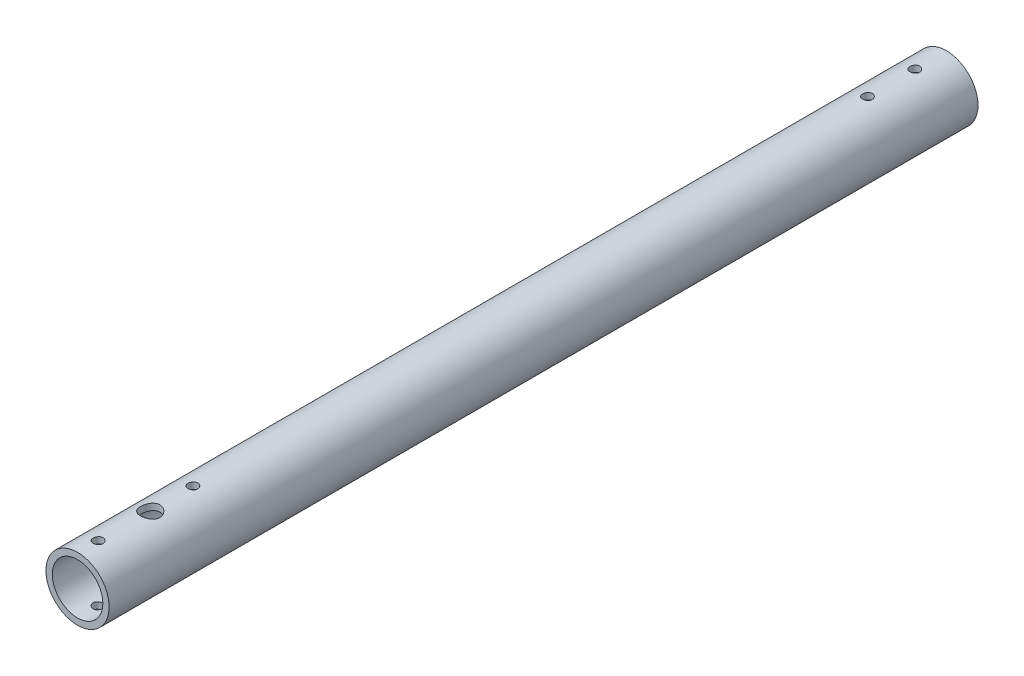
SolidWorks part; units mm, degrees
material "Thornel Mat VMA"
ref_plane "前视基准面" through (0, 0, 0) normal (0, 0, 1) x (1, 0, 0)
ref_plane "上视基准面" through (0, 0, 0) normal (0, 1, 0) x (1, 0, 0)
ref_plane "右视基准面" through (0, 0, 0) normal (1, 0, 0) x (0, 0, -1)
other "Configuration Table"
sketch "草图1" plane through (0, 0, 0) normal (0, 0, 1) x (1, 0, 0)
  circle A0 centre (0, 0) radius 10
  circle A2 centre (0, 0) radius 8
  dimension "D1" = 20
  dimension "D2" = 16
extrude "凸台-拉伸1" add sketch "草图1" along normal blind 275
sketch "草图4" plane through (0, 0, 0) normal (0, 1, 0) x (1, 0, 0)
  line L0 (0, -275) -> (0, -182.0445) construction
  line L1 (-10, -275) -> (10, -275) construction
  line L2 (0, 0) -> (0, -25) construction
  circle A0 centre (0, -268.5) radius 1.55
  circle A1 centre (0, -252) radius 3.05
  circle A2 centre (0, -238.5) radius 1.55
  circle A3 centre (0, -25) radius 1.55
  circle A4 centre (0, -10) radius 1.55
  dimension "D4" = 3.1
  dimension "D5" = 6.1
  dimension "D6" = 3.1
  dimension "D7" = 3.1
  dimension "D8" = 3.1
  dimension "D1" = 6.5
  dimension "D2" = 16.5
  dimension "D3" = 13.5
  dimension "D9" = 10
  dimension "D10" = 15
extrude "切除-拉伸1" cut sketch "草图4" against normal through all and the other way through all
